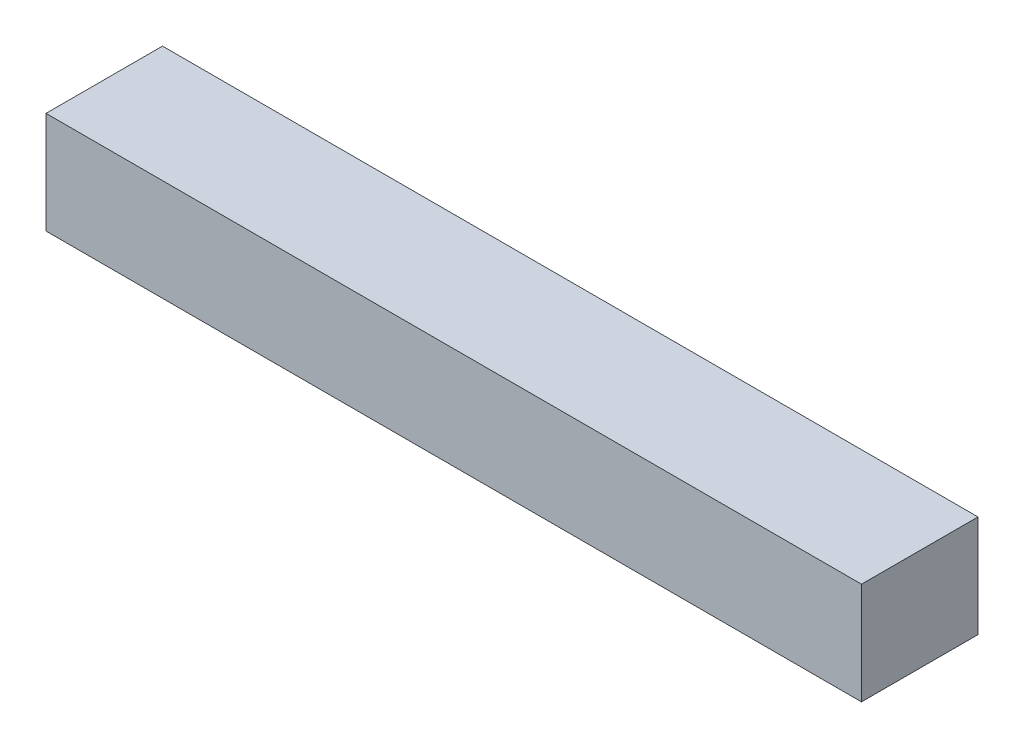
SolidWorks part; units mm, degrees
material "AISI 4130 Steel, normalized at 870C"
ref_plane "Front Plane" through (0, 0, 0) normal (0, 0, 1) x (1, 0, 0)
ref_plane "Top Plane" through (0, 0, 0) normal (0, 1, 0) x (1, 0, 0)
ref_plane "Right Plane" through (0, 0, 0) normal (1, 0, 0) x (0, 0, -1)
sketch "Sketch1" plane through (0, 0, 0) normal (1, 0, 0) x (0, 0, -1)
  line L1 (-7.6704, -4.0496) -> (-15.6704, -4.0496)
  line L2 (-7.6704, -4.0496) -> (-7.6704, -11.0496)
  line L3 (-7.6704, -11.0496) -> (-15.6704, -11.0496)
  line L4 (-15.6704, -4.0496) -> (-15.6704, -11.0496)
extrude "Boss-Extrude1" add sketch "Sketch1" along normal blind 56
